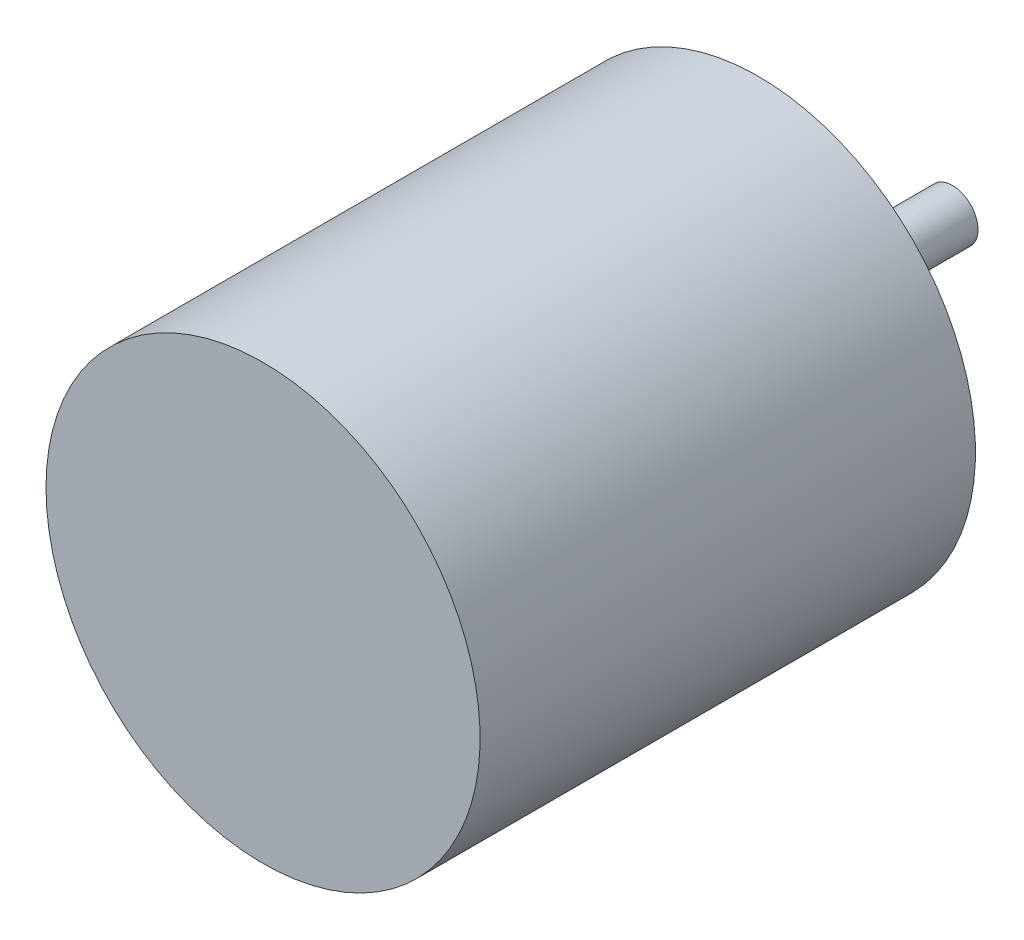
SolidWorks part; units mm, degrees
material "Motor D4250"
ref_plane "Plano frontal" through (0, 0, 0) normal (0, 0, 1) x (1, 0, 0)
ref_plane "Plano superior" through (0, 0, 0) normal (0, 1, 0) x (1, 0, 0)
ref_plane "Plano direito" through (0, 0, 0) normal (1, 0, 0) x (0, 0, -1)
sketch "Esboço1" plane through (0, 0, 0) normal (0, 0, 1) x (1, 0, 0)
  circle A0 centre (0, 0) radius 21.25
  dimension "D1" = 42.5
extrude "Ressalto-extrusão1" add sketch "Esboço1" along normal mid plane 48.5
sketch "Esboço2" plane through (0, 0, -24.25) normal (0, 0, -1) x (-1, 0, 0)
  circle A0 centre (0, 0) radius 2.5
  dimension "D1" = 5
extrude "Ressalto-extrusão2" add sketch "Esboço2" along normal blind 19
sketch "Esboço3" plane through (0, 0, -24.25) normal (0, 0, -1) x (-1, 0, 0)
  circle A0 centre (0, 0) radius 12.5 construction
  circle A1 centre (-8.6728, 9.0018) radius 1.5
  circle A2 centre (9.0018, 8.6728) radius 1.5
  circle A3 centre (8.6728, -9.0018) radius 1.5
  circle A4 centre (-9.0018, -8.6728) radius 1.5
  point P14 (0, 0)
  dimension "D1" = 25
  dimension "D2" = 3
  dimension "D3" = 4
extrude "Corte-extrusão1" cut sketch "Esboço3" against normal blind 2
